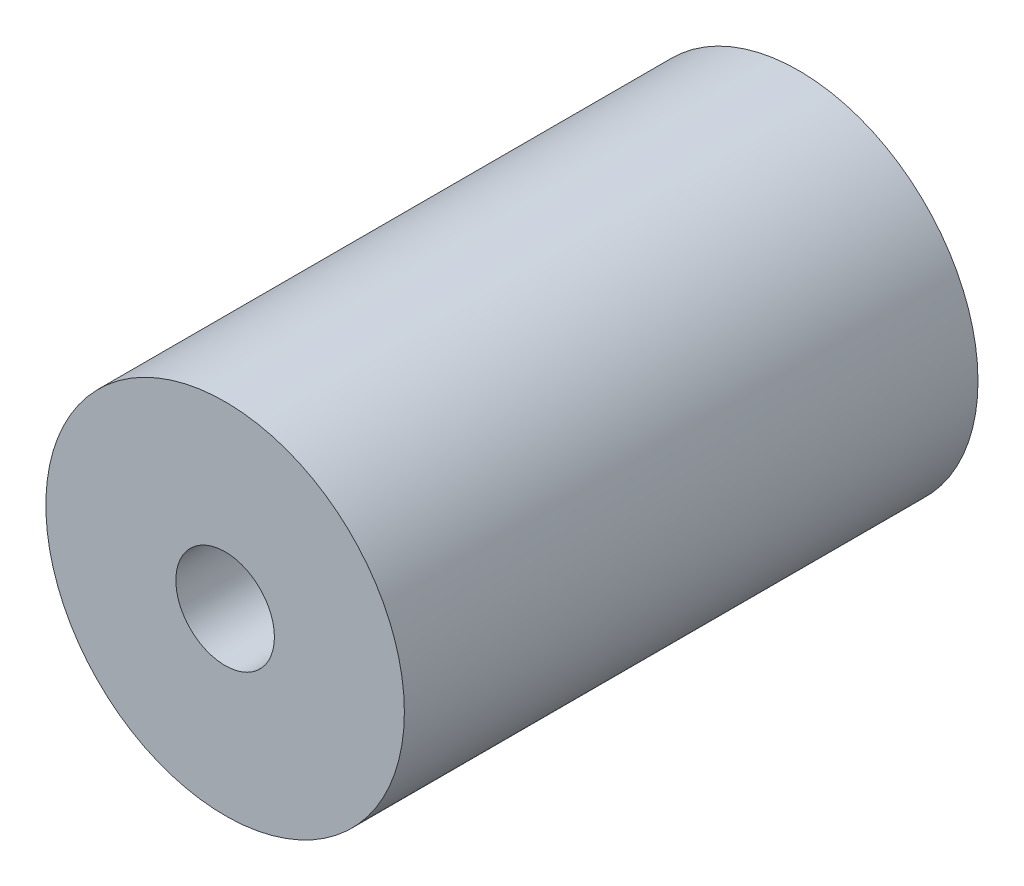
SolidWorks part; units mm, degrees
material "3.3547 (EN-AW 5083)"
ref_plane "Ebene vorne" through (0, 0, 0) normal (0, 0, 1) x (1, 0, 0)
ref_plane "Ebene oben" through (0, 0, 0) normal (0, 1, 0) x (1, 0, 0)
ref_plane "Ebene rechts" through (0, 0, 0) normal (1, 0, 0) x (0, 0, -1)
sketch "Skizze1" plane through (0, 0, 0) normal (0, 0, 1) x (1, 0, 0)
  circle A0 centre (0, 0) radius 2.75
  circle A1 centre (0, 0) radius 10
  dimension "D1" = 20
  dimension "D2" = 5.5
extrude "Aufsatz-Linear austragen1" add sketch "Skizze1" along normal blind 32
